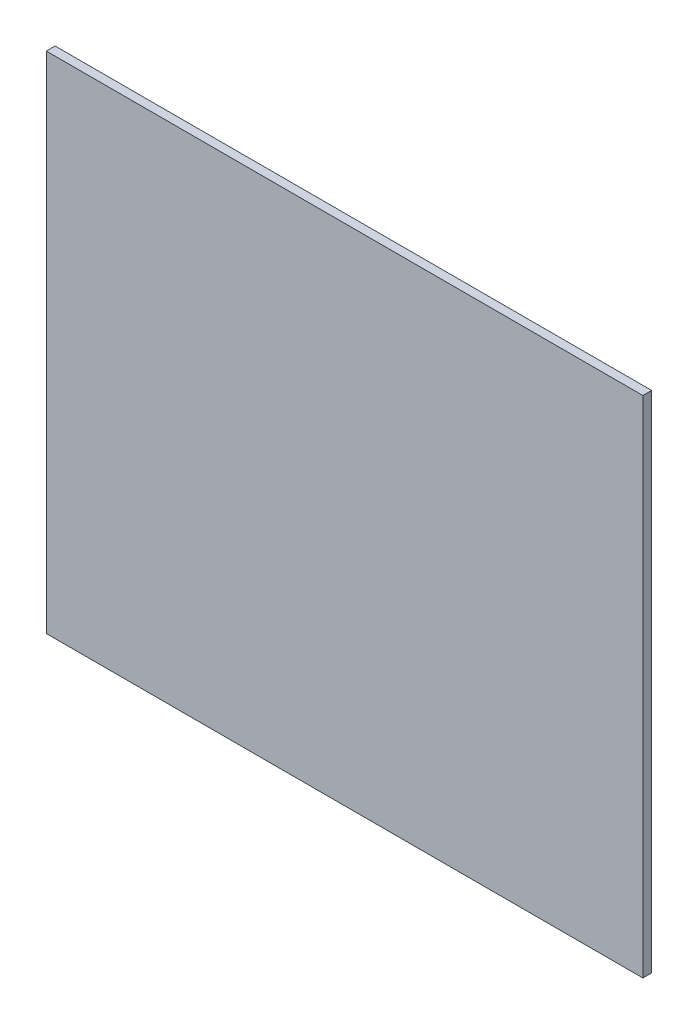
SolidWorks part; units mm, degrees
ref_plane "Alzado" through (0, 0, 0) normal (0, 0, 1) x (1, 0, 0)
ref_plane "Planta" through (0, 0, 0) normal (0, 1, 0) x (1, 0, 0)
ref_plane "Vista lateral" through (0, 0, 0) normal (1, 0, 0) x (0, 0, -1)
sketch "Croquis1" plane through (0, 0, 0) normal (0, 0, 1) x (1, 0, 0)
  line L1 (-340, -287.5) -> (340, -287.5)
  line L2 (-340, -287.5) -> (-340, 287.5)
  line L3 (-340, 287.5) -> (340, 287.5)
  line L4 (340, -287.5) -> (340, 287.5)
  line L5 (-340, -287.5) -> (340, 287.5) construction
  line L6 (-340, 287.5) -> (340, -287.5) construction
  point P0 (0, 0)
  dimension "D1" = 680
  dimension "D2" = 575
extrude "Saliente-Extruir1" add sketch "Croquis1" along normal blind 10
